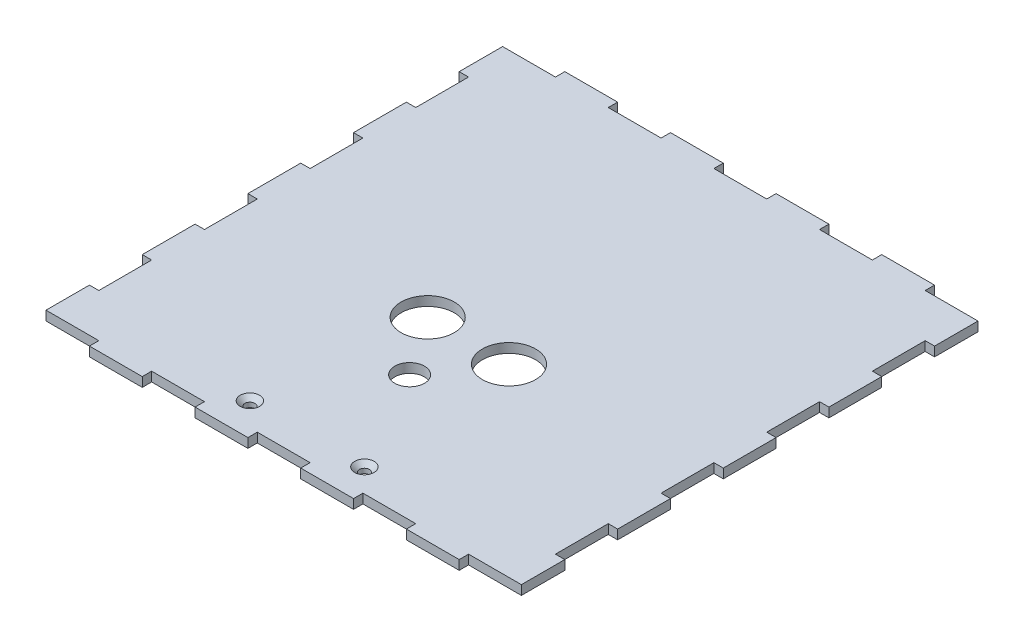
SolidWorks part; units mm, degrees
ref_plane "Front Plane" through (0, 0, 0) normal (0, 0, 1) x (1, 0, 0)
ref_plane "Top Plane" through (0, 0, 0) normal (0, 1, 0) x (1, 0, 0)
ref_plane "Right Plane" through (0, 0, 0) normal (1, 0, 0) x (0, 0, -1)
sketch "Sketch1" plane through (0, 0, 0) normal (0, 1, 0) x (1, 0, 0)
  line L0 (-76, -73) -> (-59.1111, -73)
  line L1 (-76, -76) -> (76, -76) construction
  line L2 (-76, -76) -> (-76, 76) construction
  line L3 (-76, 76) -> (76, 76) construction
  line L4 (76, -76) -> (76, 76) construction
  line L5 (0, 76) -> (0, -76) construction
  line L6 (-76, 0) -> (76, 0) construction
  line L7 (-59.1111, -73) -> (-59.1111, -76)
  line L8 (-59.1111, -76) -> (-42.2222, -76)
  line L9 (-42.2222, -76) -> (-42.2222, -73)
  line L10 (-42.2222, -73) -> (-25.3333, -73)
  line L11 (-25.3333, -73) -> (-25.3333, -76)
  line L12 (-25.3333, -76) -> (-8.4444, -76)
  line L13 (-8.4444, -76) -> (-8.4444, -73)
  line L14 (-8.4444, -73) -> (0, -73)
  line L15 (0, -73) -> (0, 0)
  line L16 (0, 0) -> (-76, 0)
  line L17 (-76, 0) -> (-76, -8.4444)
  line L18 (-76, -8.4444) -> (-73, -8.4444)
  line L19 (-73, -8.4444) -> (-73, -25.3333)
  line L20 (-73, -25.3333) -> (-76, -25.3333)
  line L21 (-76, -25.3333) -> (-76, -42.2222)
  line L22 (-76, -42.2222) -> (-73, -42.2222)
  line L23 (-73, -42.2222) -> (-73, -59.1111)
  line L24 (-73, -59.1111) -> (-76, -59.1111)
  line L25 (-76, -59.1111) -> (-76, -73)
  point P140 (0, 0)
  dimension "D1" = 152
  dimension "D2" = 3
  dimension "D3" = 3
  dimension "D4" = 16.8889
  dimension "D5" = 13.8889
extrude "Boss-Extrude1" add sketch "Sketch1" along normal blind 3
mirror "Mirror1" about plane through (0, 0, 0) normal (1, 0, 0) of "Boss-Extrude1"
sketch "Sketch2" plane through (0, 3, 0) normal (0, 1, 0) x (1, 0, 0)
  line L0 (-13, -13.96) -> (13, -13.96) construction
  line L1 (-25.3333, -76) -> (-8.4444, -76) construction
  line L2 (25.3333, -76) -> (8.4444, -76) construction
  circle A0 centre (-13, -13.96) radius 8.5
  circle A1 centre (13, -13.96) radius 8.5
  circle A2 centre (0, -32.73) radius 4.75
  point P2 (0, -13.96)
  point P8 (0, 0)
  dimension "D2" = 17
  dimension "D3" = 9.5
  dimension "D1" = 26
  dimension "D4" = 43.27
  dimension "D5" = 62.04
extrude "Cut-Extrude1" cut sketch "Sketch2" against normal through all
sketch "Sketch3" plane through (0, 3, 0) normal (0, 1, 0) x (1, 0, 0)
  line L0 (-18.3, -65.5) -> (18.3, -65.5) construction
  line L1 (-25.3333, -76) -> (-8.4444, -76) construction
  circle A0 centre (-18.3, -65.5) radius 1.6
  circle A1 centre (18.3, -65.5) radius 1.6
  point P2 (0, -65.5)
  dimension "D1" = 3.2
  dimension "D2" = 36.6
  dimension "D3" = 10.5
extrude "Cut-Extrude2" cut sketch "Sketch3" against normal through all
chamfer "Chamfer1" distance 1.5 angle 45 2 edges at (18.3, 3, 67.1) (-18.3, 3, 67.1)
